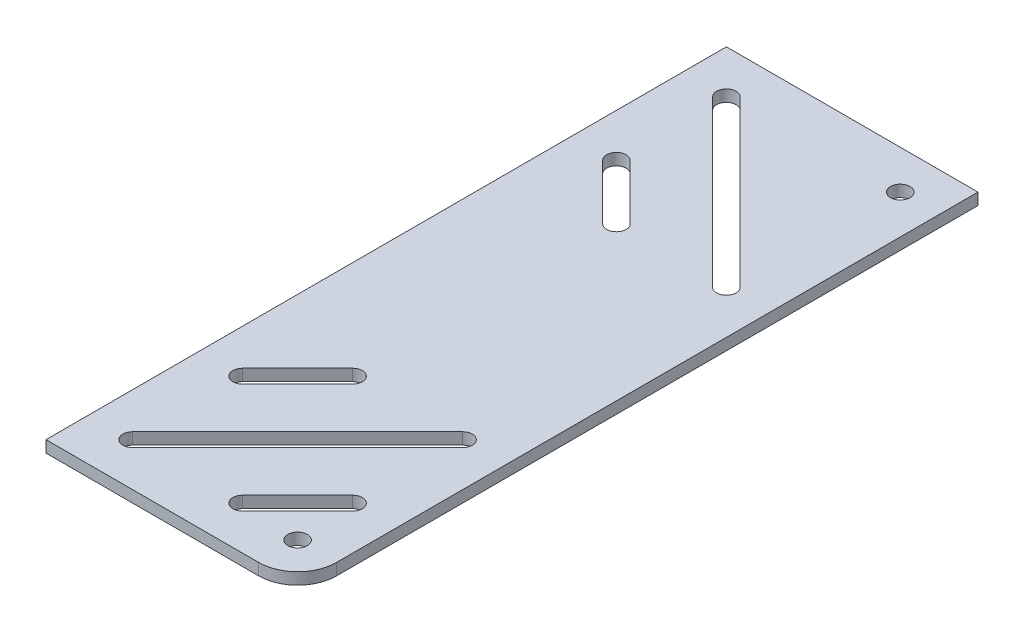
SolidWorks part; units mm, degrees
material "Custom Plastic"
ref_plane "Plan de face" through (0, 0, 0) normal (0, 0, 1) x (1, 0, 0)
ref_plane "Plan de dessus" through (0, 0, 0) normal (0, 1, 0) x (1, 0, 0)
ref_plane "Plan de droite" through (0, 0, 0) normal (1, 0, 0) x (0, 0, -1)
sketch "Esquisse1" plane through (0, 0, 0) normal (0, 1, 0) x (1, 0, 0)
  line L0 (125.7087, 87.5) -> (180.4225, 87.5)
  line L4 (190.4225, 87.5) -> (190.4225, -67.5) construction
  line L5 (190.4225, 87.5) -> (-109.5775, 87.5) construction
  line L7 (190.4225, 77.5) -> (190.4225, -77.5)
  line L8 (180.4225, -87.5) -> (125.7087, -87.5)
  line L10 (125.7087, 87.5) -> (125.7087, -87.5)
  line L11 (180.4225, 87.5) -> (190.4225, 87.5)
  line L12 (180.4225, 87.5) -> (180.4225, 77.5) construction
  line L13 (180.4225, 77.5) -> (190.4225, 77.5) construction
  line L14 (190.4225, -77.5) -> (180.4225, -77.5) construction
  line L15 (180.4225, -77.5) -> (180.4225, -87.5) construction
  line L16 (125.7087, 84.5) -> (125.7087, 87.5) construction
  line L17 (190.4225, 87.5) -> (190.4225, 77.5)
  line L20 (180.4225, 87.5) -> (180.4225, -87.5) construction
  line L21 (-109.5775, -87.5) -> (180.4225, -87.5) construction
  line L22 (125.7087, 77.5) -> (125.7087, -49922.5) construction
  line L23 (190.4225, -77.5) -> (190.4225, 87.5) construction
  arc A2 (180.4225, 87.5) -> (190.4225, 77.5) centre (180.4225, 77.5) cw construction
  arc A3 (190.4225, -77.5) -> (180.4225, -87.5) centre (180.4225, -77.5) cw
  circle A6 centre (180.4225, 77.5) radius 2.5
  circle A7 centre (180.4225, -77.5) radius 2.5
  point P22 (180.4225, 0)
  dimension "D4" = 5
  dimension "D6" = 10
extrude "Boss.-Extru.1" add sketch "Esquisse1" along normal blind 3
sketch "Esquisse2" plane through (0, 3, 0) normal (0, 1, 0) x (1, 0, 0)
  line L0 (125.7087, -87.5) -> (190.4225, -22.7862) construction
  line L1 (138.6202, -49.8398) -> (135.0846, -46.3043) construction
  line L2 (190.4225, -77.5) -> (190.4225, 87.5) construction
  line L8 (138.6202, -78.1241) -> (135.0846, -74.5886) construction
  line L9 (177.511, -32.1622) -> (181.0466, -35.6977) construction
  line L10 (138.6202, -78.1241) -> (181.0466, -35.6977)
  line L11 (135.0846, -74.5886) -> (177.511, -32.1622)
  line L12 (159.8334, -56.9109) -> (156.2978, -53.3754) construction
  line L13 (166.9044, -78.1241) -> (163.3689, -74.5886) construction
  line L14 (177.511, -60.4464) -> (181.0466, -63.982) construction
  line L15 (166.9044, -78.1241) -> (181.0466, -63.982)
  line L16 (163.3689, -74.5886) -> (177.511, -60.4464)
  line L17 (173.9755, -71.053) -> (170.44, -67.5175) construction
  line L18 (167.7535, -64.831) -> (160.0777, -57.1552) construction
  line L19 (181.7788, -23.4211) -> (181.7788, 49976.5789) construction
  line L20 (134.3524, -80.9589) -> (134.3524, 49919.0411) construction
  line L21 (125.3963, -78.8563) -> (175.3623, -78.8563) construction
  line L22 (184.9094, -31.4299) -> (134.9433, -31.4299) construction
  line L23 (149.2268, -32.1622) -> (152.7623, -35.6977) construction
  line L24 (138.6202, -49.8398) -> (152.7623, -35.6977)
  line L25 (135.0846, -46.3043) -> (149.2268, -32.1622)
  line L26 (145.6912, -42.7688) -> (142.1557, -39.2332) construction
  line L27 (125.7087, 87.5) -> (190.4225, 22.7862) construction
  line L28 (190.4225, 87.5) -> (125.7087, 87.5) construction
  line L31 (173.9755, 71.053) -> (170.44, 67.5175) construction
  line L32 (177.511, 60.4464) -> (181.0466, 63.982) construction
  line L35 (166.9044, 78.1241) -> (163.3689, 74.5886) construction
  line L38 (159.8334, 56.9109) -> (156.2978, 53.3754) construction
  line L39 (177.511, 32.1622) -> (181.0466, 35.6977) construction
  line L42 (138.6202, 78.1241) -> (135.0846, 74.5886) construction
  line L43 (135.0846, 74.5886) -> (177.511, 32.1622)
  line L44 (138.6202, 78.1241) -> (181.0466, 35.6977)
  line L50 (163.3689, 74.5886) -> (177.511, 60.4464) construction
  line L51 (166.9044, 78.1241) -> (181.0466, 63.982) construction
  line L52 (145.6912, 42.7688) -> (142.1557, 39.2332) construction
  line L53 (149.2268, 32.1622) -> (152.7623, 35.6977) construction
  line L54 (138.6202, 49.8398) -> (135.0846, 46.3043) construction
  line L55 (135.0846, 46.3043) -> (149.2268, 32.1622)
  line L56 (138.6202, 49.8398) -> (152.7623, 35.6977)
  line L57 (84.2748, 31.4299) -> (50084.2748, 31.4299) construction
  line L58 (84.2748, 78.8563) -> (50084.2748, 78.8563) construction
  line L59 (128.208, 25.2855) -> (-26894.0993, -26997.0218) construction
  arc A2 (135.0846, -74.5886) -> (138.6202, -78.1241) centre (136.8524, -76.3563) ccw
  arc A3 (177.511, -32.1622) -> (181.0466, -35.6977) centre (179.2788, -33.9299) cw
  arc A4 (163.3689, -74.5886) -> (166.9044, -78.1241) centre (165.1367, -76.3563) ccw
  arc A5 (177.511, -60.4464) -> (181.0466, -63.982) centre (179.2788, -62.2142) cw
  arc A6 (135.0846, -46.3043) -> (138.6202, -49.8398) centre (136.8524, -48.0721) ccw
  arc A7 (149.2268, -32.1622) -> (152.7623, -35.6977) centre (150.9945, -33.9299) cw
  arc A16 (177.511, 32.1622) -> (181.0466, 35.6977) centre (179.2788, 33.9299) ccw
  arc A17 (135.0846, 74.5886) -> (138.6202, 78.1241) centre (136.8524, 76.3563) cw
  arc A20 (177.511, 60.4464) -> (181.0466, 63.982) centre (179.2788, 62.2142) ccw construction
  arc A21 (163.3689, 74.5886) -> (166.9044, 78.1241) centre (165.1367, 76.3563) cw construction
  arc A22 (149.2268, 32.1622) -> (152.7623, 35.6977) centre (150.9945, 33.9299) ccw
  arc A23 (135.0846, 46.3043) -> (138.6202, 49.8398) centre (136.8524, 48.0721) cw
  point P22 (158.0656, -55.1431)
  point P26 (158.0656, -55.1431)
  point P35 (172.2077, -69.2853)
  point P55 (143.9235, -41.001)
  point P74 (158.0656, 55.1431)
  point P79 (158.0656, 55.1431)
  point P89 (172.2077, 69.2853)
  point P98 (143.9235, 41.001)
  dimension "D3" = 5
  dimension "D4" = 60
  dimension "D5" = 20
  dimension "D6" = 45
  dimension "D7" = 45
extrude "Enlèv. mat.-Extru.1" cut sketch "Esquisse2" against normal through all
